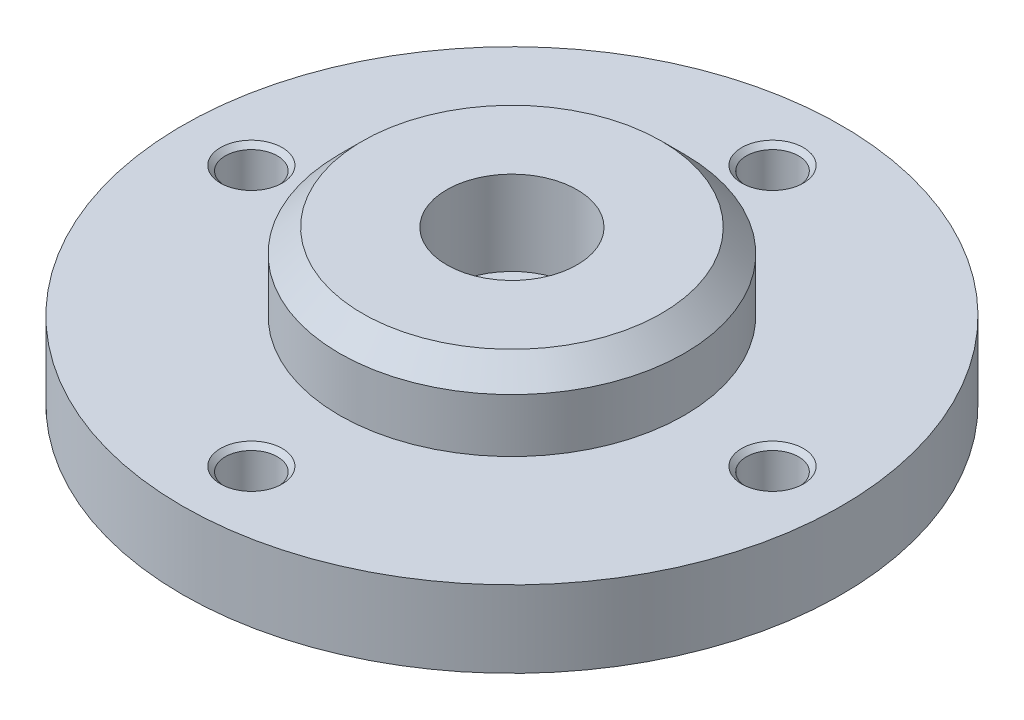
SolidWorks part; units mm, degrees
ref_plane "Front Plane" through (0, 0, 0) normal (0, 0, 1) x (1, 0, 0)
ref_plane "Top Plane" through (0, 0, 0) normal (0, 1, 0) x (1, 0, 0)
ref_plane "Right Plane" through (0, 0, 0) normal (1, 0, 0) x (0, 0, -1)
sketch "Sketch1" plane through (0, 0, 0) normal (0, 0, 1) x (1, 0, 0)
  line L0 (43, 0) -> (43, 10)
  line L1 (43, 10) -> (22.5, 10)
  line L2 (22.5, 10) -> (22.5, 20)
  line L3 (22.5, 20) -> (8.5, 20)
  line L5 (5, 3) -> (25, 3)
  line L6 (25, 3) -> (25, 0)
  line L7 (25, 0) -> (43, 0)
  line L8 (0, 0) -> (0, -12.1924) construction
  line L9 (5, 9) -> (5, 3)
  line L10 (8.5, 20) -> (8.5, 9)
  line L11 (8.5, 9) -> (5, 9)
  dimension "D1" = 3
  dimension "D2" = 86
  dimension "D3" = 50
  dimension "D4" = 10
  dimension "D5" = 10
  dimension "D6" = 45
  dimension "D7" = 20
  dimension "D8" = 17
  dimension "D9" = 11
revolve "Revolve1" add sketch "Sketch1" angle 360 about L8
sketch "Sketch3" plane through (0, 10, 0) normal (0, 1, 0) x (1, 0, 0)
  circle A0 centre (0, 0) radius 34 construction
  circle A1 centre (34, 0) radius 2.5
  circle A2 centre (0, -34) radius 2.5
  circle A3 centre (-34, 0) radius 2.5
  circle A4 centre (0, 34) radius 2.5
  point P14 (0, 0)
  dimension "D2" = 5
  dimension "D3" = 68
  dimension "D1" = 4
extrude "Cut-Extrude1" cut sketch "Sketch3" against normal blind 10
chamfer "Chamfer1" distance 3 angle 45 1 edges at (0, 20, 22.5)
hole_wizard "M8 Tapped Hole1" positions "3DSketch1" profile "Sketch4" tap size "M8" standard "ISO"
sketch3d "3DSketch1"
  line L0 (0, 0, -34) -> (0, 10, -34) construction
  line L1 (34, 0, 0) -> (34, 10, 0) construction
  line L2 (0, 0, 34) -> (0, 10, 34) construction
  line L3 (-34, 0, 0) -> (-34, 10, 0) construction
  point P0 (0, 10, -34)
  point P4 (34, 10, 0)
  point P8 (0, 10, 34)
  point P12 (-34, 10, 0)
sketch "Sketch4" plane through (0, 10, -34) normal (1, 0, 0) x (0, 0, 1)
  line L0 (0, 0) -> (0, 21.7929)
  line L1 (0, 21.7929) -> (3.4, 19.75)
  line L2 (3.4, 19.75) -> (3.4, 0.625)
  line L3 (3.4, 0.625) -> (4.025, 0)
  line L5 (4.025, 0) -> (0, 0)
  line L6 (-3.4, 0.625) -> (-4.025, 0) construction
  line L10 (0, 21.7929) -> (-3.4, 19.75) construction
  line L11 (0, -6.35) -> (0, 107.95) construction
  dimension "Tap Drill Dia." = 6.8
  dimension "Tap Drill Depth" = 19.75
  dimension "Near C'Sink Dia." = 8.05
  dimension "Near C'Sink Angle" = 90
  dimension "Drill Angle" = 118
cosmetic thread "Hole Thread1" parameters "D1"=16, "D2"=8
cosmetic thread "Hole Thread2" parameters "D1"=16, "D2"=8
cosmetic thread "Hole Thread3" parameters "D1"=16, "D2"=8
cosmetic thread "Hole Thread4" parameters "D1"=16, "D2"=8
